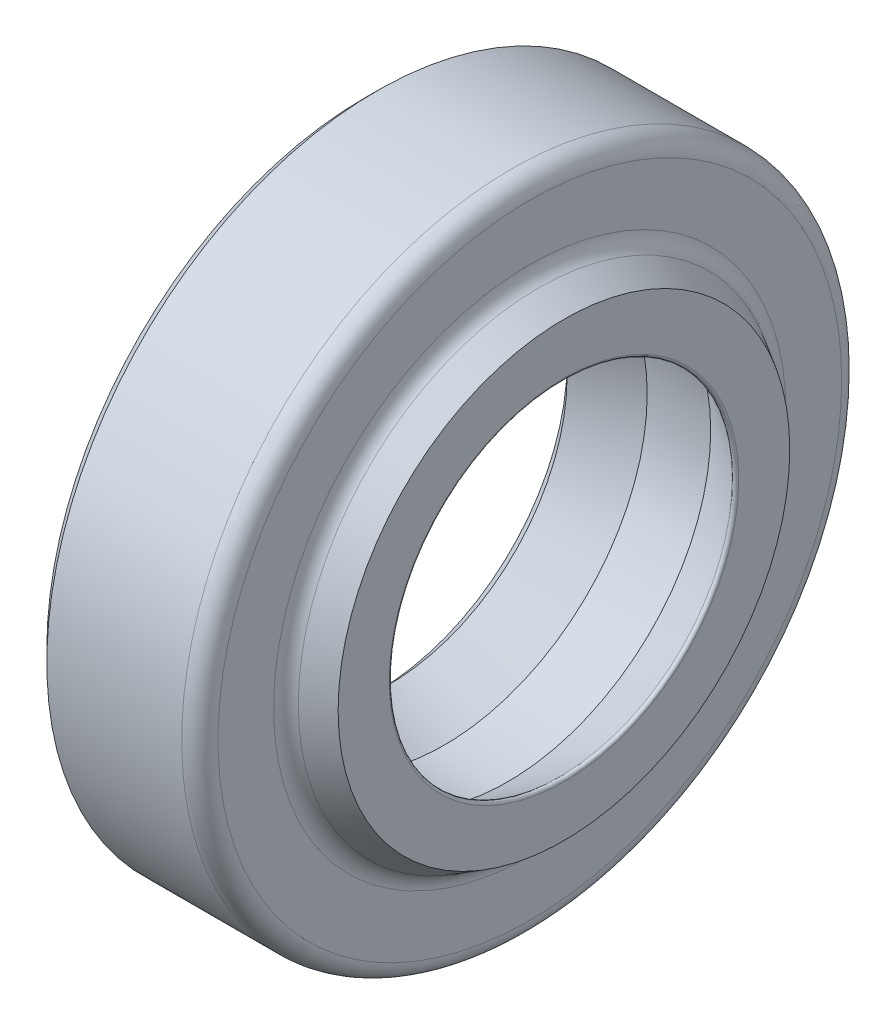
SolidWorks part; units mm, degrees
ref_plane "Front Plane" through (0, 0, 0) normal (0, 0, 1) x (1, 0, 0)
ref_plane "Top Plane" through (0, 0, 0) normal (0, 1, 0) x (1, 0, 0)
ref_plane "Right Plane" through (0, 0, 0) normal (1, 0, 0) x (0, 0, -1)
sketch "Sketch1" plane through (0, 0, 0) normal (0, 0, 1) x (1, 0, 0)
  line L0 (-2.3453, 5.555) -> (-0.6327, 6.35)
  line L1 (-0.6327, 6.35) -> (1.3537, 6.35)
  line L2 (1.3537, 6.35) -> (2.9835, 5.3965)
  line L3 (3.1115, 5.4699) -> (3.1115, 7.0655)
  line L4 (3.1115, 7.0655) -> (2.3255, 7.5254)
  line L5 (2.0447, 8.015) -> (2.0447, 9.7579)
  line L6 (-2.7428, 10.3251) -> (1.4775, 10.3251)
  line L7 (-0.6327, 10.3251) -> (-0.6327, 6.35) construction
  line L8 (-2.7428, 10.3251) -> (-3.1115, 9.9564)
  line L9 (-3.1115, 9.9564) -> (-3.1115, 9.0133)
  line L10 (-3.1115, 9.0133) -> (-0.8669, 8.6168)
  line L11 (-0.8669, 8.0583) -> (-2.7428, 7.7269)
  line L12 (-2.7428, 7.7269) -> (-2.7428, 5.9525)
  line L13 (-2.7428, 5.9525) -> (-2.3453, 5.555)
  line L14 (-3.1115, 0) -> (3.1115, 0) construction
  line L15 (-0.6327, 8.3375) -> (-0.9162, 8.3375) construction
  line L16 (-0.6327, 6.35) -> (-0.6327, 5.555) construction
  line L17 (-0.6327, 5.9525) -> (-2.7428, 5.9525) construction
  line L18 (-0.6327, 5.555) -> (-3.1115, 5.555) construction
  line L19 (3.1115, 8.6168) -> (-3.1115, 8.6168) construction
  line L21 (2.0447, 7.874) -> (2.0447, -7.874) construction
  arc A0 (2.9835, 5.3965) -> (3.1115, 5.4699) centre (3.0264, 5.4699) ccw
  arc A1 (2.3255, 7.5254) -> (2.0447, 8.015) centre (2.6119, 8.015) cw
  arc A2 (2.0447, 9.7579) -> (1.4775, 10.3251) centre (1.4775, 9.7579) ccw
  arc A3 (-0.8669, 8.6168) -> (-0.8669, 8.0583) centre (-0.9162, 8.3375) cw
  point P31 (2.0447, 8.015)
  point P40 (2.0447, 0)
  dimension "D3" = 0.2836
  dimension "D4" = 0.5672
  dimension "D5" = 0.0851
  dimension "Seal Width" = 5.1562
  dimension "O'all Seal Width" = 6.223
  dimension "OD" = 20.6502
  dimension "ID" = 12.7
  dimension "D7" = 45
  dimension "D6" = 0.3687
  dimension "D1" = 3.9751
  dimension "D8" = 1.3118
  dimension "D9" = 4.7701
  dimension "D10" = 0.795
  dimension "D11" = 0.7155
  dimension "Groove Shoulder Dia" = 15.748
revolve "Revolve1" add sketch "Sketch1" angle 360 about L14
equation "\"D4@Sketch1\"=\"Seal Width@Sketch1\"*.11"
equation "\"D5@Sketch1\"=\"D4@Sketch1\"*.15"
equation "\"D6@Sketch1\"=\"D4@Sketch1\"*.65"
equation "\"D3@Sketch1\"=\"D4@Sketch1\"/2"
equation "\"D8@Sketch1\"=\"D1@Sketch1\"*.33"
equation "\"D9@Sketch1\"=\"D1@Sketch1\"*1.2"
equation "\"D11@Sketch1\"=\"D10@Sketch1\"*.9"
